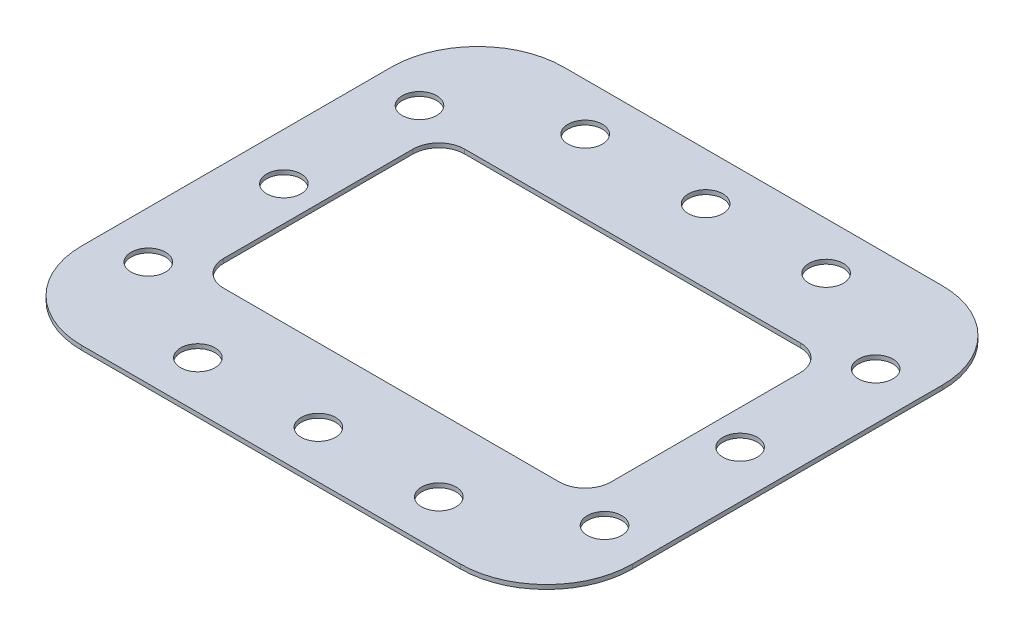
SolidWorks part; units mm, degrees
ref_plane "前视基准面" through (0, 0, 0) normal (0, 0, 1) x (1, 0, 0)
ref_plane "上视基准面" through (0, 0, 0) normal (0, 1, 0) x (1, 0, 0)
ref_plane "右视基准面" through (0, 0, 0) normal (1, 0, 0) x (0, 0, -1)
sketch "草图1" plane through (0, 0, 0) normal (0, 1, 0) x (1, 0, 0)
  line L0 (-79.3496, 0) -> (84.813, 0) construction
  line L1 (-44, -56) -> (44, -56)
  line L2 (-64, -36) -> (-64, 36)
  line L3 (-44, 56) -> (44, 56)
  line L4 (64, -36) -> (64, 36)
  line L5 (-64, -56) -> (64, 56) construction
  line L6 (-64, 56) -> (64, -56) construction
  line L7 (0, -88.7154) -> (0, 79.3496) construction
  line L9 (-39, -28) -> (39, -28)
  line L10 (-45, -22) -> (-45, 22)
  line L11 (-39, 28) -> (39, 28)
  line L12 (45, -22) -> (45, 22)
  line L13 (-45, -28) -> (45, 28) construction
  line L14 (-45, 28) -> (45, -28) construction
  arc A0 (-44, -56) -> (-64, -36) centre (-44, -36) cw
  arc A1 (64, -36) -> (44, -56) centre (44, -36) cw
  arc A2 (44, 56) -> (64, 36) centre (44, 36) cw
  arc A3 (-44, 56) -> (-64, 36) centre (-44, 36) ccw
  circle A4 centre (-28, 45) radius 4
  circle A5 centre (0, 45) radius 4
  circle A6 centre (28, 45) radius 4
  circle A7 centre (-53, 31.5) radius 4
  circle A8 centre (-53, 0) radius 4
  circle A9 centre (-53, -31.5) radius 4
  circle A10 centre (53, 31.5) radius 4
  circle A11 centre (53, 0) radius 4
  circle A12 centre (53, -31.5) radius 4
  circle A13 centre (28, -45) radius 4
  circle A14 centre (0, -45) radius 4
  circle A15 centre (-28, -45) radius 4
  arc A16 (-39, -28) -> (-45, -22) centre (-39, -22) cw
  arc A17 (39, -28) -> (45, -22) centre (39, -22) ccw
  arc A18 (45, 22) -> (39, 28) centre (39, 22) ccw
  arc A19 (-39, 28) -> (-45, 22) centre (-39, 22) ccw
  point P0 (0, 0)
  point P46 (0, 0)
  dimension "D3" = 20
  dimension "D5" = 8
  dimension "D7" = 8
  dimension "D9" = 8
  dimension "D10" = 8
  dimension "D13" = 6
  dimension "D1" = 128
  dimension "D2" = 112
  dimension "D4" = 11
  dimension "D6" = 28
  dimension "D8" = 53
  dimension "D11" = 90
  dimension "D12" = 56
  dimension "D14" = 63
extrude "凸台-拉伸1" add sketch "草图1" along normal blind 1
